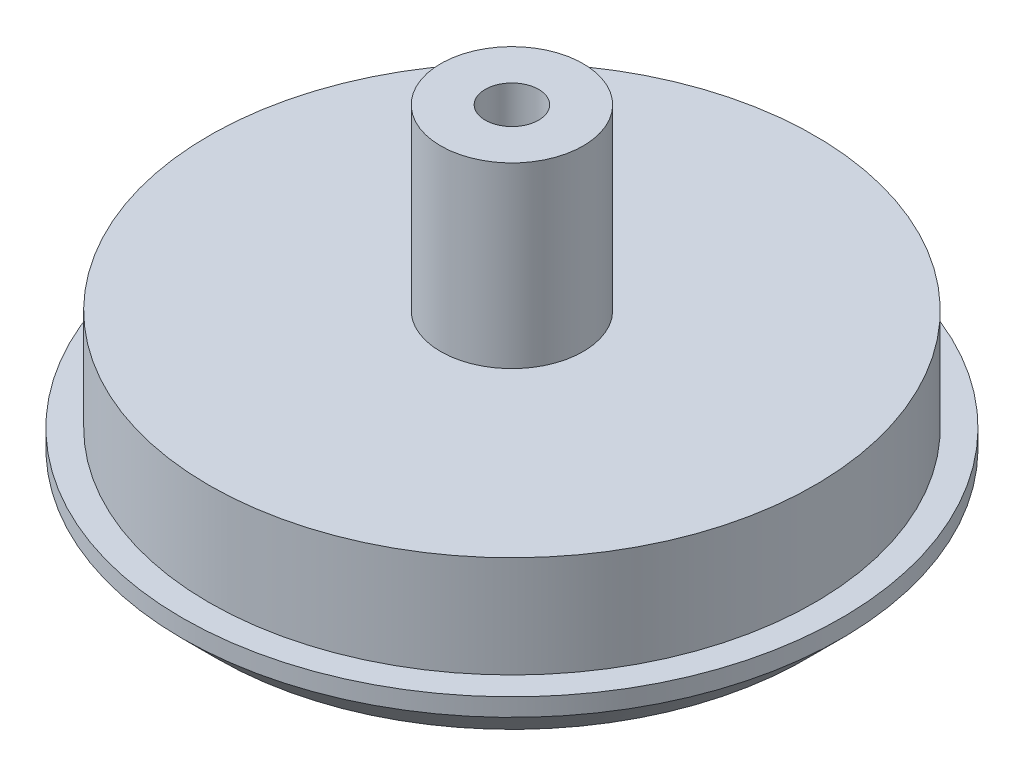
SolidWorks part; units mm, degrees
ref_plane "Front Plane" through (0, 0, 0) normal (0, 0, 1) x (1, 0, 0)
ref_plane "Top Plane" through (0, 0, 0) normal (0, 1, 0) x (1, 0, 0)
ref_plane "Right Plane" through (0, 0, 0) normal (1, 0, 0) x (0, 0, -1)
sketch "Sketch1" plane through (0, 0, 0) normal (0, 1, 0) x (1, 0, 0)
  circle A0 centre (0, 0) radius 18.5
  dimension "D1" = 37
extrude "Boss-Extrude1" add sketch "Sketch1" along normal blind 8.7
sketch "Sketch2" plane through (0, 8.7, 0) normal (0, 1, 0) x (1, 0, 0)
  circle A0 centre (0, 0) radius 17
  circle A1 centre (0, 0) radius 18.5 construction
  circle A2 centre (0, 0) radius 18.5
  dimension "D1" = 34
extrude "Cut-Extrude1" cut sketch "Sketch2" against normal offset from surface (5.7 mm away) 3 up to face at (0, 0, 18.5)
sketch "Sketch3" plane through (0, 0, 0) normal (0, -1, 0) x (1, 0, 0)
  circle A0 centre (0, 0) radius 14.2
  dimension "D1" = 28.4
extrude "Cut-Extrude2" cut sketch "Sketch3" against normal blind 5.6
sketch "Sketch4" plane through (0, 8.7, 0) normal (0, 1, 0) x (1, 0, 0)
  circle A0 centre (0, 0) radius 4
  dimension "D1" = 8
extrude "Boss-Extrude2" add sketch "Sketch4" along normal blind 10
chamfer "Chamfer1" distance 2 angle 45 1 edges at (0, 0, 18.5)
sketch "Sketch5" plane through (0, 5.6, 0) normal (0, -1, 0) x (1, 0, 0)
  circle A0 centre (0, 0) radius 1.5
  dimension "D1" = 3
extrude "Cut-Extrude3" cut sketch "Sketch5" against normal through all
